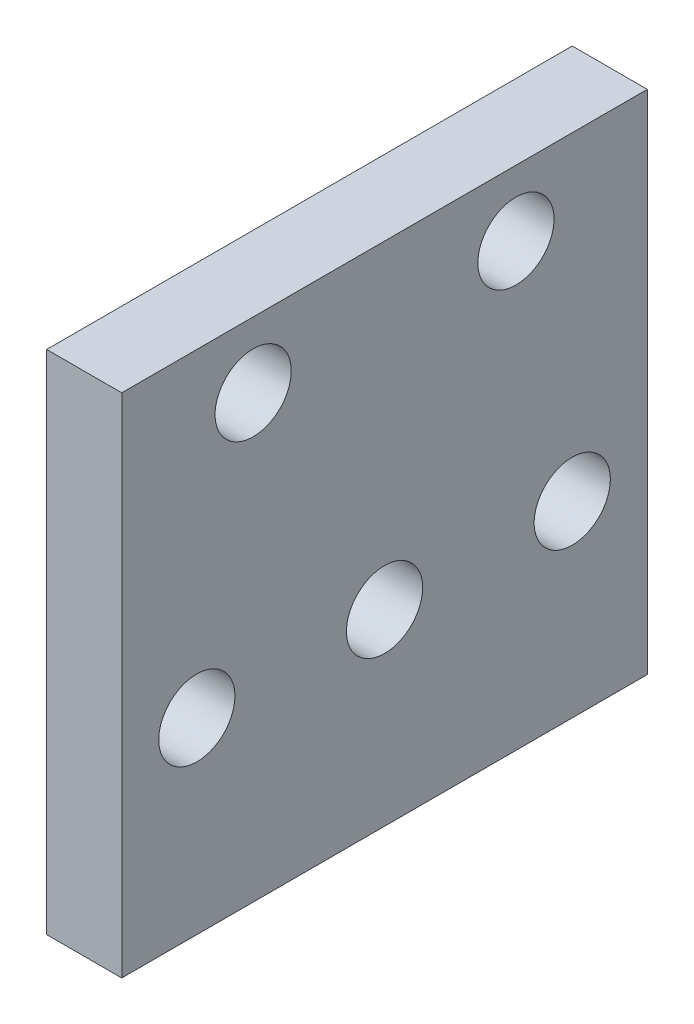
SolidWorks part; units mm, degrees
ref_plane "Front" through (0, 0, 0) normal (0, 0, 1) x (1, 0, 0)
ref_plane "Top" through (0, 0, 0) normal (0, 1, 0) x (1, 0, 0)
ref_plane "Right" through (0, 0, 0) normal (1, 0, 0) x (0, 0, -1)
sketch "Sketch1" plane through (0, 0, 0) normal (1, 0, 0) x (0, 0, -1)
  line L1 (-17.78, -17.145) -> (17.78, -17.145)
  line L2 (-17.78, -17.145) -> (-17.78, 17.145)
  line L3 (-17.78, 17.145) -> (17.78, 17.145)
  line L4 (17.78, -17.145) -> (17.78, 17.145)
  line L5 (-17.78, -17.145) -> (17.78, 17.145) construction
  line L6 (-17.78, 17.145) -> (17.78, -17.145) construction
  point P0 (0, 0)
  dimension "D1" = 35.56
  dimension "D2" = 34.29
extrude "Boss-Extrude1" add sketch "Sketch1" along normal blind 5.08
sketch "Sketch2" plane through (5.08, 0, 0) normal (1, 0, 0) x (0, 0, -1)
  line L0 (-17.78, 8.255) -> (17.78, 8.255) construction
  line L1 (-17.78, 17.145) -> (-17.78, -17.145) construction
  line L2 (17.78, -17.145) -> (17.78, 17.145) construction
  line L3 (-17.78, -17.145) -> (17.78, -17.145) construction
  line L4 (0, 8.255) -> (0, 17.145) construction
  line L5 (17.78, 17.145) -> (-17.78, 17.145) construction
  line L6 (0, 12.7) -> (-17.78, 12.7) construction
  line L7 (0, 12.7) -> (17.78, 12.7) construction
  line L8 (0, 8.255) -> (0, -17.145) construction
  line L9 (-12.7, -4.445) -> (12.7, -4.445) construction
  circle A0 centre (-8.89, 12.7) radius 2.5781
  circle A1 centre (8.89, 12.7) radius 2.5781
  circle A2 centre (-12.7, -4.445) radius 2.5781
  circle A3 centre (0, -4.445) radius 2.5781
  circle A4 centre (12.7, -4.445) radius 2.5781
  point P23 (0, -4.445)
  point P27 (0, 0)
  point P28 (0, 12.7)
  dimension "D2" = 5.1562
  dimension "D3" = 5.1562
  dimension "D5" = 5.1562
  dimension "D1" = 25.4
  dimension "D4" = 25.4
extrude "Cut-Extrude1" cut sketch "Sketch2" against normal through all
